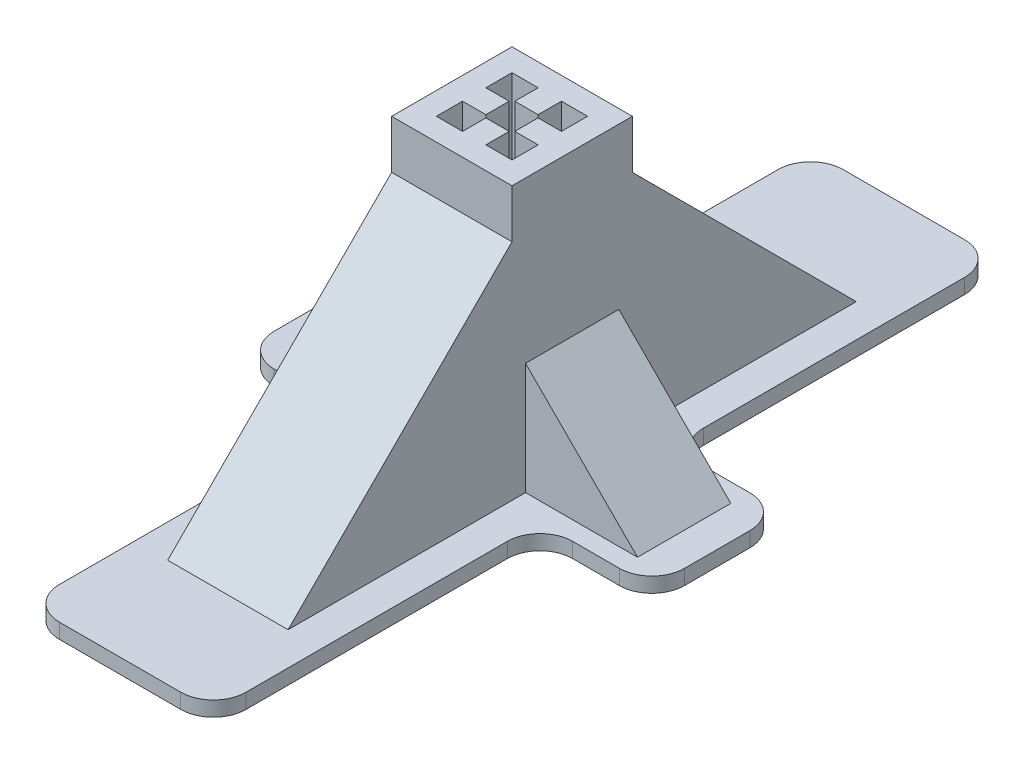
SolidWorks part; units mm, degrees
ref_plane "Front Plane" through (0, 0, 0) normal (0, 0, 1) x (1, 0, 0)
ref_plane "Top Plane" through (0, 0, 0) normal (0, 1, 0) x (1, 0, 0)
ref_plane "Right Plane" through (0, 0, 0) normal (1, 0, 0) x (0, 0, -1)
sketch "Sketch2" plane through (0, 0, 0) normal (0, 1, 0) x (1, 0, 0)
  line L0 (-3.125, 10.125) -> (-3.125, 3.875)
  line L1 (10.125, -10.125) -> (-10.125, -10.125) construction
  line L2 (10.125, -10.125) -> (10.125, 10.125) construction
  line L3 (10.125, 10.125) -> (-10.125, 10.125) construction
  line L4 (-10.125, -10.125) -> (-10.125, 10.125) construction
  line L5 (10.125, -10.125) -> (-10.125, 10.125) construction
  line L6 (10.125, 10.125) -> (-10.125, -10.125) construction
  line L7 (-3.125, 3.875) -> (3.125, 3.875)
  line L8 (3.125, 3.875) -> (3.125, 10.125)
  line L9 (10.125, 3.125) -> (3.875, 3.125)
  line L10 (3.875, 3.125) -> (3.875, -3.125)
  line L11 (3.875, -3.125) -> (10.125, -3.125)
  line L12 (3.125, -10.125) -> (3.125, -3.875)
  line L13 (3.125, -3.875) -> (-3.125, -3.875)
  line L14 (-3.125, -3.875) -> (-3.125, -10.125)
  line L15 (-10.125, -3.125) -> (-3.875, -3.125)
  line L16 (-3.875, -3.125) -> (-3.875, 3.125)
  line L17 (-3.875, 3.125) -> (-10.125, 3.125)
  line L18 (-10.125, -3.125) -> (-10.125, -10.125)
  line L19 (-10.125, 10.125) -> (-3.125, 10.125)
  line L20 (-10.125, 10.125) -> (-10.125, 3.125)
  line L21 (-10.125, -10.125) -> (-3.125, -10.125)
  line L22 (10.125, 10.125) -> (10.125, 3.125)
  line L23 (16.125, -16.125) -> (-16.125, -16.125)
  line L24 (16.125, -16.125) -> (16.125, 16.125)
  line L25 (16.125, 16.125) -> (-16.125, 16.125)
  line L26 (-16.125, -16.125) -> (-16.125, 16.125)
  line L27 (16.125, -16.125) -> (-16.125, 16.125) construction
  line L28 (16.125, 16.125) -> (-16.125, -16.125) construction
  line L29 (3.125, 10.125) -> (10.125, 10.125)
  line L30 (10.125, -3.125) -> (10.125, -10.125)
  line L31 (3.125, -10.125) -> (10.125, -10.125)
  point P0 (0, 0)
  point P10 (0, 3.875)
  point P11 (0, 0)
  point P26 (0, 0)
  dimension "D1" = 20.25
  dimension "D2" = 6.25
  dimension "D3" = 6.25
  dimension "D5" = 6
  dimension "D4" = 4
extrude "Boss-Extrude1" add sketch "Sketch2" along normal blind 75
sketch "Sketch3" plane through (0, 0, 0) normal (0, -1, 0) x (1, 0, 0)
  line L4 (-16.125, 16.125) -> (-16.125, -16.125)
  line L5 (-16.125, -16.125) -> (16.125, -16.125)
  line L6 (16.125, -16.125) -> (16.125, 16.125)
  line L7 (16.125, 16.125) -> (-16.125, 16.125)
  line L8 (-16.125, 16.125) -> (-16.125, -16.125)
  line L9 (-16.125, -16.125) -> (16.125, -16.125)
  line L10 (16.125, -16.125) -> (16.125, 16.125)
  line L11 (16.125, 16.125) -> (-16.125, 16.125)
  dimension "D1" = 0
extrude "Boss-Extrude2" add sketch "Sketch3" along normal blind 2
sketch "Sketch4" plane through (0, -2, 0) normal (0, -1, 0) x (1, 0, 0)
  line L0 (-25, 17.5) -> (-25, 105)
  line L1 (-25, -105) -> (25, -105)
  line L2 (-25, -105) -> (-25, -17.5)
  line L3 (-25, 105) -> (25, 105)
  line L4 (16.125, 16.125) -> (-16.125, 16.125)
  line L5 (-16.125, 16.125) -> (-16.125, -16.125)
  line L6 (-16.125, -16.125) -> (16.125, -16.125)
  line L7 (16.125, -16.125) -> (16.125, 16.125)
  line L8 (16.125, 16.125) -> (-16.125, 16.125)
  line L9 (-16.125, 16.125) -> (-16.125, -16.125)
  line L10 (-16.125, -16.125) -> (16.125, -16.125)
  line L11 (16.125, -16.125) -> (16.125, 16.125)
  line L12 (25, -105) -> (25, -17.5)
  line L13 (-25, -17.5) -> (-55, -17.5)
  line L15 (-25, 17.5) -> (-55, 17.5)
  line L16 (-55, -17.5) -> (-55, 17.5)
  line L17 (25, -17.5) -> (55, -17.5)
  line L19 (25, 17.5) -> (55, 17.5)
  line L20 (55, -17.5) -> (55, 17.5)
  line L21 (25, 17.5) -> (25, 105)
  point P8 (0, 105)
  point P11 (-55, 0)
  point P20 (55, 0)
  dimension "D2" = 50
  dimension "D3" = 210
  dimension "D4" = 30
  dimension "D5" = 35
  dimension "D1" = 0
extrude "Boss-Extrude3" add sketch "Sketch4" against normal blind 4
fillet "Fillet1" radius 8.75 12 edges at (-55, 0, -17.5) (-55, 0, 17.5) (-25, 0, 105) (25, 0, 105) (55, 0, 17.5) (55, 0, -17.5) (25, 0, -105) (-25, 0, -105) (25, 0, 17.5) (25, 0, -17.5) (-25, 0, -17.5) (-25, 0, 17.5)
sketch "Sketch5" plane through (16.125, 0, 0) normal (1, 0, 0) x (0, 0, -1)
  line L0 (16.125, 62) -> (76.125, 2)
  line L1 (16.125, 75) -> (16.125, 2) construction
  line L2 (96.25, 2) -> (26.25, 2) construction
  line L3 (76.125, 2) -> (16.125, 2)
  line L4 (16.125, 2) -> (16.125, 62)
  line L5 (-16.125, 62) -> (-76.125, 2)
  line L6 (-16.125, 75) -> (-16.125, 2) construction
  line L7 (-26.25, 2) -> (-96.25, 2) construction
  line L8 (-76.125, 2) -> (-16.125, 2)
  line L9 (-16.125, 2) -> (-16.125, 62)
  dimension "D1" = 60
extrude "Boss-Extrude4" add sketch "Sketch5" against normal up to surface (32.25 mm away) up to face at (-16.125, 38.5, 0)
sketch "Sketch7" plane through (0, 0, 0) normal (0, 0, 1) x (1, 0, 0)
  line L0 (-16.125, 2) -> (-46.125, 2)
  line L1 (-16.125, 2) -> (-16.125, 62) construction
  line L2 (-46.125, 2) -> (-16.125, 32)
  line L3 (-16.125, 32) -> (-16.125, 2)
  line L4 (-33.75, 2) -> (-46.25, 2) construction
  line L5 (0, 2) -> (0, 62) construction
  line L6 (-16.125, 2) -> (16.125, 2) construction
  line L7 (-16.125, 62) -> (16.125, 62) construction
  line L8 (46.125, 2) -> (16.125, 32)
  line L9 (16.125, 2) -> (46.125, 2)
  line L10 (16.125, 32) -> (16.125, 2)
  dimension "D1" = 30
extrude "Boss-Extrude12" add sketch "Sketch7" along normal mid plane 25
